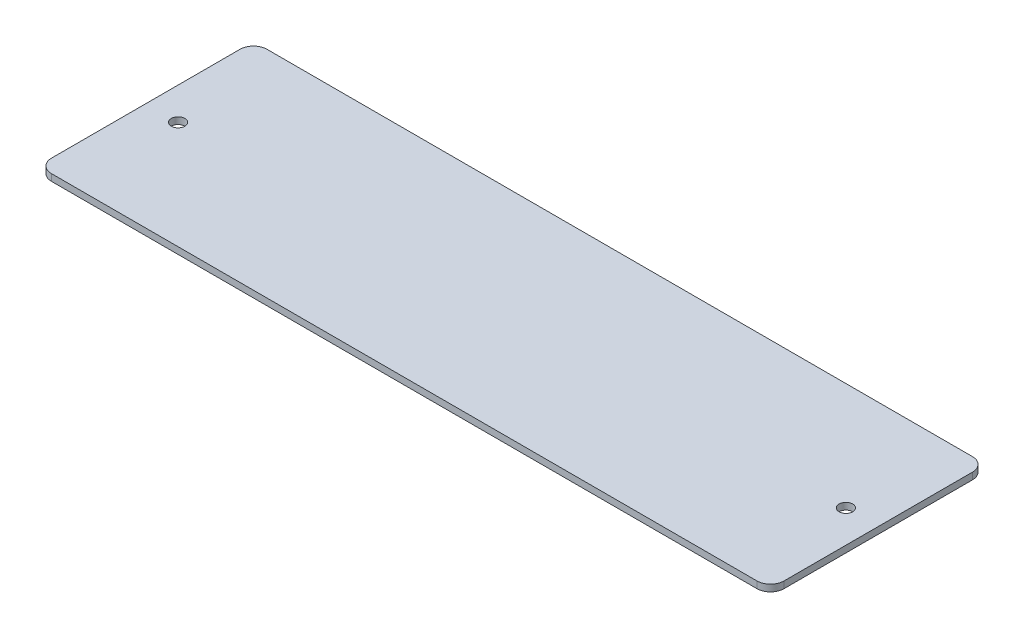
SolidWorks part; units mm, degrees
material "Acrylic (Medium-high impact)"
ref_plane "Front Plane" through (0, 0, 0) normal (0, 0, 1) x (1, 0, 0)
ref_plane "Top Plane" through (0, 0, 0) normal (0, 1, 0) x (1, 0, 0)
ref_plane "Right Plane" through (0, 0, 0) normal (1, 0, 0) x (0, 0, -1)
sketch "Sketch1" plane through (0, 0, 0) normal (0, 1, 0) x (1, 0, 0)
  line L0 (78.74, 0) -> (-78.74, 0) construction
  line L1 (-86.36, -25.4) -> (86.36, -25.4)
  line L2 (-86.36, -25.4) -> (-86.36, 25.4)
  line L3 (-86.36, 25.4) -> (86.36, 25.4)
  line L4 (86.36, -25.4) -> (86.36, 25.4)
  line L5 (-86.36, -25.4) -> (86.36, 25.4) construction
  line L6 (-86.36, 25.4) -> (86.36, -25.4) construction
  circle A0 centre (-78.74, 0) radius 1.6002
  circle A1 centre (78.74, 0) radius 1.6002
  point P0 (0, 0)
  point P9 (0, 0)
  dimension "D4" = 3.2004
  dimension "D1" = 172.72
  dimension "D2" = 50.8
  dimension "D3" = 157.48
extrude "Boss-Extrude1" add sketch "Sketch1" along normal blind 1.5875
fillet "Fillet1" radius 3.175 4 edges at (86.36, 0.7937, -25.4) (86.36, 0.7937, 25.4) (-86.36, 0.7937, -25.4) (-86.36, 0.7937, 25.4)
